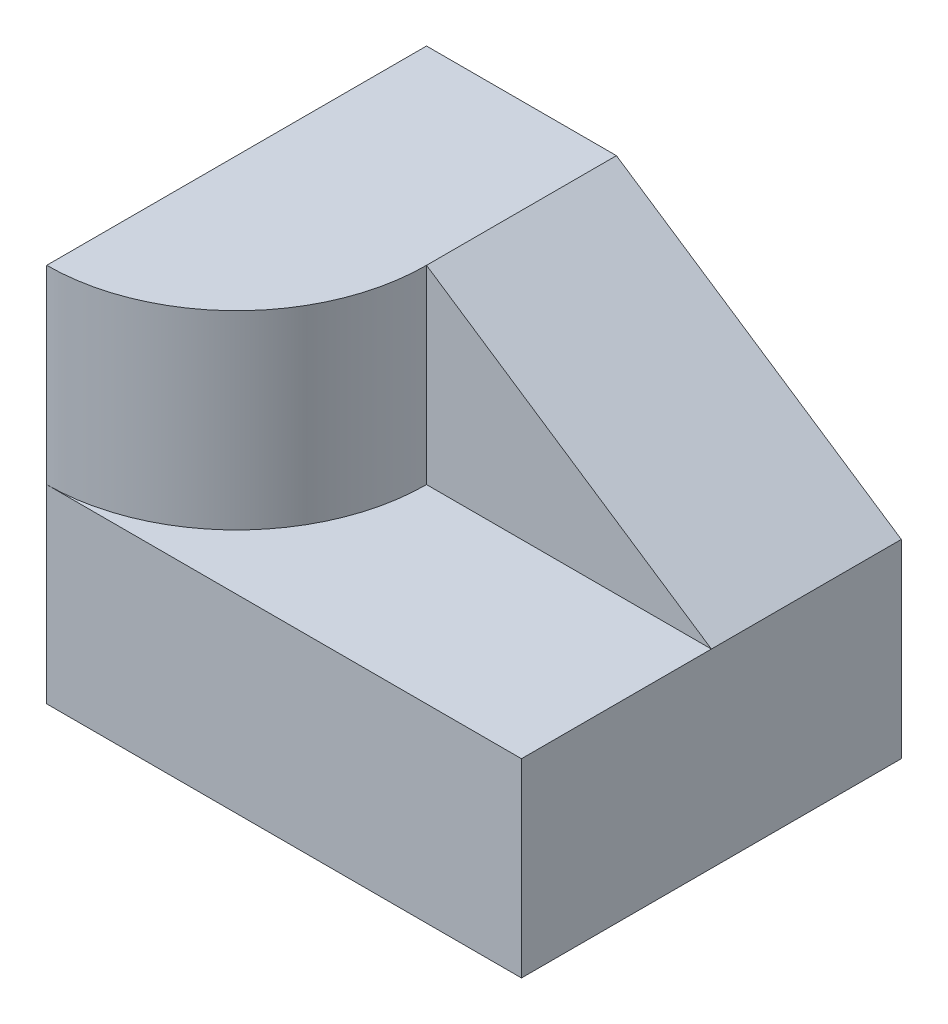
SolidWorks part; units mm, degrees
ref_plane "Front Plane" through (0, 0, 0) normal (0, 0, 1) x (1, 0, 0)
ref_plane "Top Plane" through (0, 0, 0) normal (0, 1, 0) x (1, 0, 0)
ref_plane "Right Plane" through (0, 0, 0) normal (1, 0, 0) x (0, 0, -1)
sketch "Sketch1" plane through (0, 0, 0) normal (0, 1, 0) x (1, 0, 0)
  line L1 (-25, 20) -> (25, 20)
  line L2 (-25, 20) -> (-25, -20)
  line L3 (-25, -20) -> (25, -20)
  line L4 (25, 20) -> (25, -20)
  line L5 (-25, 20) -> (25, -20) construction
  line L6 (-25, -20) -> (25, 20) construction
  point P0 (0, 0)
  dimension "D1" = 40
  dimension "D2" = 50
extrude "Boss-Extrude1" add sketch "Sketch1" along normal blind 20
sketch "Sketch2" plane through (0, 20, 0) normal (0, 1, 0) x (1, 0, 0)
  line L0 (-25, 20) -> (-5, 20)
  line L1 (25, 20) -> (-25, 20) construction
  line L2 (-5, 20) -> (-5, 0)
  line L3 (-25, -20) -> (25, -20) construction
  line L6 (-25, -20) -> (-25, 20)
  arc A0 (-25, -20) -> (-5, 0) centre (-25, 0) ccw
  point P12 (-5, -20)
  dimension "D2" = 20
  dimension "D1" = 20
extrude "Boss-Extrude2" add sketch "Sketch2" along normal blind 20 contours L2 A0 L6 L0
sketch "Sketch3" plane through (0, 0, -20) normal (0, 0, -1) x (-1, 0, 0)
  line L0 (5, 40) -> (-25, 20)
  line L1 (-25, 20) -> (5, 20)
  line L2 (5, 20) -> (5, 40)
extrude "Boss-Extrude3" add sketch "Sketch3" against normal blind 20
